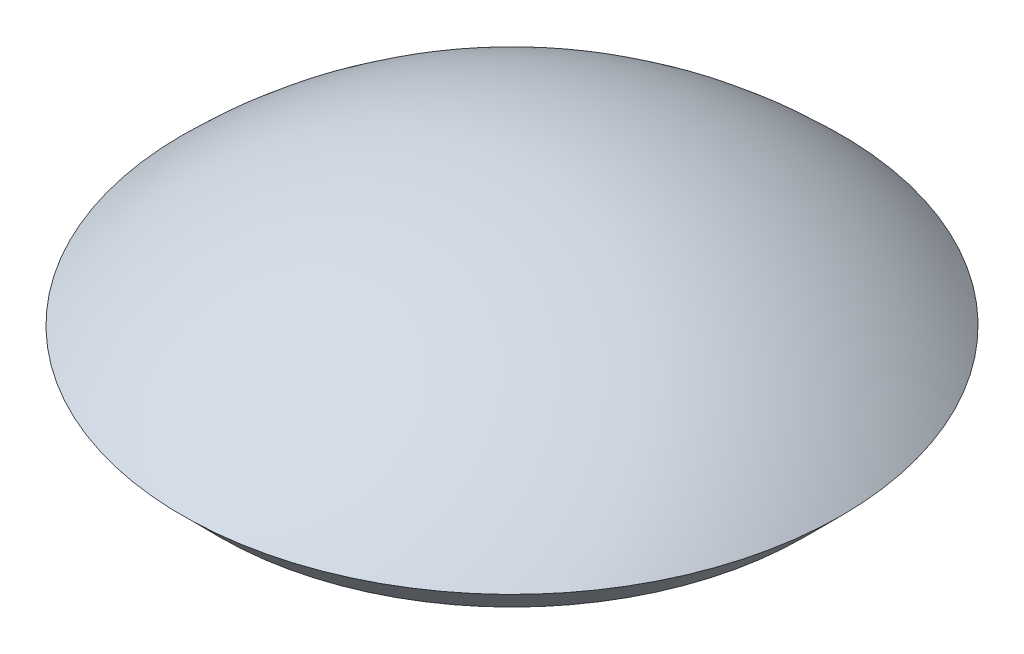
SolidWorks part; units mm, degrees
ref_plane "Alzado" through (0, 0, 0) normal (0, 0, 1) x (1, 0, 0)
ref_plane "Planta" through (0, 0, 0) normal (0, 1, 0) x (1, 0, 0)
ref_plane "Vista lateral" through (0, 0, 0) normal (1, 0, 0) x (0, 0, -1)
sketch "Croquis1" plane through (0, 0, 0) normal (0, 0, 1) x (1, 0, 0)
  line L0 (0, -25) -> (0, -50) construction
  line L1 (-1.5, -25) -> (1.5, -25) construction
  line L2 (-1.5, -25) -> (-1.5, 25) construction
  line L3 (-1.5, 25) -> (1.5, 25) construction
  line L4 (1.5, -25) -> (1.5, 25) construction
  line L5 (-1.5, -25) -> (1.5, 25) construction
  line L6 (-1.5, 25) -> (1.5, -25) construction
  line L7 (0, -50) -> (19.9494, -30.0506) construction
  line L8 (19.9494, -30.0506) -> (17.6777, -32.3223)
  line L9 (0, -21.7874) -> (0, -25)
  arc A0 (17.6777, -32.3223) -> (0, -25) centre (0, -50) ccw
  arc A1 (19.9494, -30.0506) -> (0, -21.7874) centre (0, -50) ccw
  point P0 (0, 0)
  dimension "D1" = 50
  dimension "D2" = 3
  dimension "D3" = 25
revolve "Revolución1" add sketch "Croquis1" angle 360 about L0
